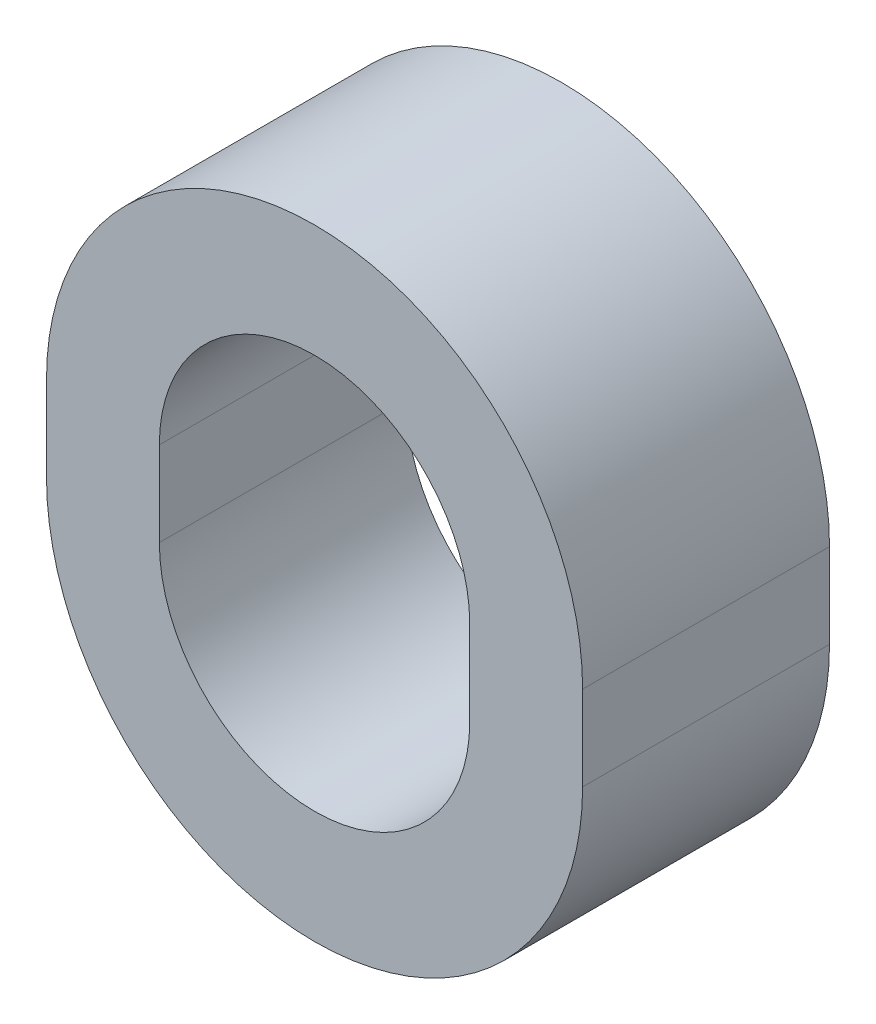
SolidWorks part; units mm, degrees
ref_plane "Спереди" through (0, 0, 0) normal (0, 0, 1) x (1, 0, 0)
ref_plane "Сверху" through (0, 0, 0) normal (0, 1, 0) x (1, 0, 0)
ref_plane "Справа" through (0, 0, 0) normal (1, 0, 0) x (0, 0, -1)
sketch "Эскиз1" plane through (0, 0, 0) normal (0, 0, 1) x (1, 0, 0)
  line L0 (0, 0) -> (0, 6) construction
  line L1 (0, 0) -> (50.0645, 0) construction
  line L2 (-19, -3) -> (-19, 3)
  line L3 (19, -3) -> (19, 3)
  line L4 (-11, -3) -> (-11, 3)
  line L5 (11, -3) -> (11, 3)
  arc A0 (19, 3) -> (-19, 3) centre (0, 3) ccw
  arc A1 (11, 3) -> (-11, 3) centre (0, 3) ccw
  arc A2 (11, -3) -> (-11, -3) centre (0, -3) cw
  arc A3 (19, -3) -> (-19, -3) centre (0, -3) cw
  dimension "D1" = 38
  dimension "D3" = 22
  dimension "D2" = 3
extrude "Вытянуть1" add sketch "Эскиз1" along normal blind 17.5
